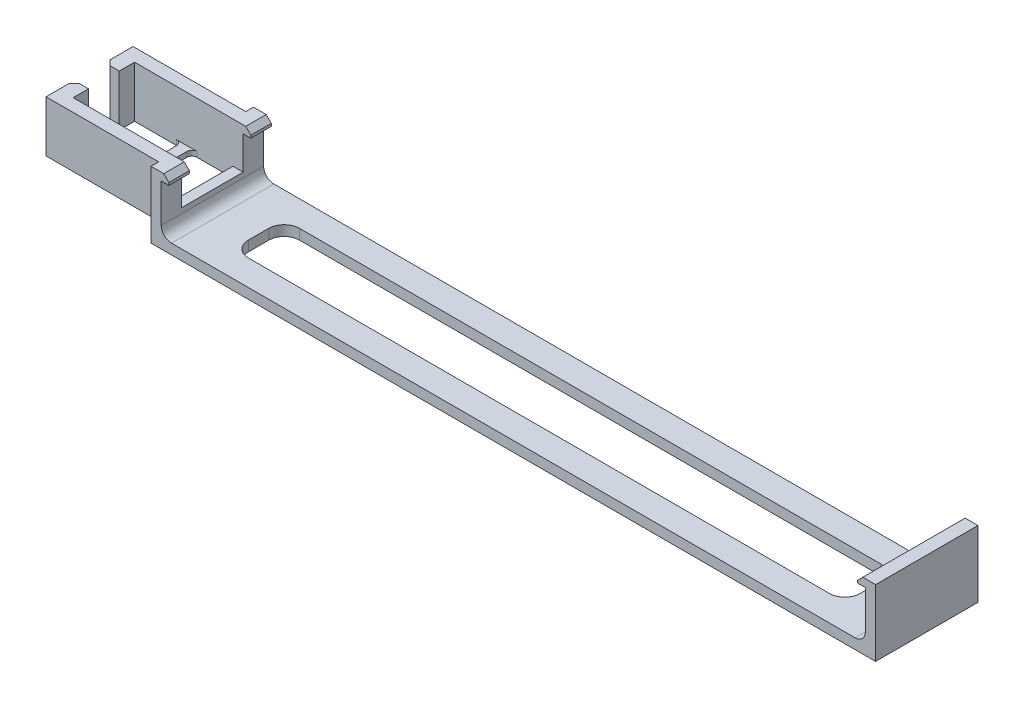
SolidWorks part; units mm, degrees
ref_plane "Front Plane" through (0, 0, 0) normal (0, 0, 1) x (1, 0, 0)
ref_plane "Top Plane" through (0, 0, 0) normal (0, 1, 0) x (1, 0, 0)
ref_plane "Right Plane" through (0, 0, 0) normal (1, 0, 0) x (0, 0, -1)
sketch "Sketch1" plane through (0, 0, 0) normal (0, 1, 0) x (1, 0, 0)
  line L1 (-70.75, 10) -> (70.75, 10)
  line L2 (-70.75, 10) -> (-70.75, -10)
  line L3 (-70.75, -10) -> (70.75, -10)
  line L4 (70.75, 10) -> (70.75, -10)
  line L5 (-70.75, 10) -> (70.75, -10) construction
  line L6 (-70.75, -10) -> (70.75, 10) construction
  point P0 (0, 0)
  dimension "D1" = 141.5
  dimension "D2" = 20
extrude "Boss-Extrude1" add sketch "Sketch1" along normal blind 2
sketch "Sketch2" plane through (0, 2, 0) normal (0, 1, 0) x (1, 0, 0)
  line L0 (-70.75, -10) -> (70.75, -10) construction
  line L1 (70.75, 10) -> (68.75, 10)
  line L2 (70.75, 10) -> (70.75, -10)
  line L3 (70.75, -10) -> (68.75, -10)
  line L4 (68.75, 10) -> (68.75, -10)
  line L6 (-70.75, 10) -> (-68.75, 10)
  line L7 (-70.75, 10) -> (-70.75, -10)
  line L8 (-70.75, -10) -> (-68.75, -10)
  line L9 (-68.75, 10) -> (-68.75, -10)
  dimension "D1" = 2
  dimension "D2" = 2
extrude "Boss-Extrude2" add sketch "Sketch2" along normal blind 11
sketch "Sketch3" plane through (68.75, 0, 0) normal (-1, 0, 0) x (0, 0, 1)
  line L0 (-10, 13) -> (-10, 2) construction
  line L1 (10, 13) -> (-10, 13)
  line L2 (10, 13) -> (10, 11.5)
  line L3 (10, 11.5) -> (-10, 11.5)
  line L4 (-10, 13) -> (-10, 11.5)
  dimension "D1" = 1.5
extrude "Boss-Extrude3" add sketch "Sketch3" along normal blind 1.5
chamfer "Chamfer1" distance 1 angle 45 1 edges at (67.25, 13, 0)
sketch "Sketch4" plane through (-68.75, 0, 0) normal (1, 0, 0) x (0, 0, -1)
  line L0 (10, 13) -> (10, 2) construction
  line L1 (-10, 13) -> (10, 13)
  line L2 (-10, 13) -> (-10, 11.5)
  line L3 (-10, 11.5) -> (10, 11.5)
  line L4 (10, 13) -> (10, 11.5)
  dimension "D1" = 1.5
extrude "Boss-Extrude4" add sketch "Sketch4" along normal blind 1.5
chamfer "Chamfer2" distance 1 angle 45 1 edges at (-67.25, 13, 0)
sketch "Sketch5" plane through (-68.75, 0, 0) normal (1, 0, 0) x (0, 0, -1)
  line L0 (-10, 11.5) -> (-10, 2) construction
  line L1 (-6, 5) -> (6, 5)
  line L2 (-6, 5) -> (-6, 19.3249)
  line L3 (-6, 19.3249) -> (6, 19.3249)
  line L4 (6, 5) -> (6, 19.3249)
  line L5 (-10, 2) -> (10, 2) construction
  dimension "D1" = 12
  dimension "D2" = 4
  dimension "D3" = 3
extrude "Cut-Extrude1" cut sketch "Sketch5" against normal blind 11.5 and the other way blind 1.5
sketch "Sketch6" plane through (-70.75, 0, 0) normal (-1, 0, 0) x (0, 0, 1)
  line L0 (-10, 13) -> (-6, 13) construction
  line L1 (-8.5, 13) -> (-6, 13)
  line L2 (-8.5, 13) -> (-8.5, 3)
  line L3 (-8.5, 3) -> (-6, 3)
  line L4 (-6, 13) -> (-6, 3)
  line L5 (6, 13) -> (10, 13) construction
  line L6 (8.5, 13) -> (6, 13)
  line L7 (8.5, 13) -> (8.5, 3)
  line L8 (8.5, 3) -> (6, 3)
  line L9 (6, 13) -> (6, 3)
  line L10 (-6, 5) -> (6, 5) construction
  line L11 (-6, 13) -> (-6, 5) construction
  dimension "D1" = 2.5
  dimension "D2" = 2.5
  dimension "D3" = 2
  dimension "D4" = 2
  dimension "D5" = 0
extrude "Boss-Extrude5" add sketch "Sketch6" along normal blind 22
sketch "Sketch7" plane through (0, 0, 6) normal (0, 0, -1) x (-1, 0, 0)
  line L0 (92.75, 3) -> (70.75, 3) construction
  line L1 (92.75, 13) -> (89.95, 13)
  line L2 (92.75, 13) -> (92.75, 3)
  line L3 (92.75, 3) -> (89.95, 3)
  line L4 (89.95, 13) -> (89.95, 3)
  dimension "D1" = 2.8
extrude "Boss-Extrude6" add sketch "Sketch7" along normal blind 3
sketch "Sketch8" plane through (0, 0, -6) normal (0, 0, 1) x (1, 0, 0)
  line L0 (-92.75, 3) -> (-70.75, 3) construction
  line L1 (-92.75, 13) -> (-89.95, 13)
  line L2 (-92.75, 13) -> (-92.75, 3)
  line L3 (-92.75, 3) -> (-89.95, 3)
  line L4 (-89.95, 13) -> (-89.95, 3)
  dimension "D1" = 2.8
extrude "Boss-Extrude7" add sketch "Sketch8" along normal blind 3
chamfer "Chamfer3" distance 1 angle 45 2 edges at (-92.75, 8, -3) (-92.75, 8, 3)
sketch "Sketch9" plane through (0, 3, 0) normal (0, -1, 0) x (1, 0, 0)
  line L0 (-92.75, 8.5) -> (-70.75, 8.5) construction
  line L1 (-80.75, 8.5) -> (-78.75, 8.5)
  line L2 (-80.75, 8.5) -> (-80.75, -8.5)
  line L3 (-80.75, -8.5) -> (-78.75, -8.5)
  line L4 (-78.75, 8.5) -> (-78.75, -8.5)
  line L5 (-92.75, -8.5) -> (-70.75, -8.5) construction
  line L6 (-70.75, -10) -> (-70.75, 10) construction
  dimension "D1" = 2
  dimension "D2" = 8
extrude "Boss-Extrude8" add sketch "Sketch9" against normal blind 1
fillet "Fillet1" radius 1 4 edges at (-80.75, 3.5, -6) (-78.75, 3.5, -6) (-80.75, 3.5, 6) (-78.75, 3.5, 6)
fillet "Fillet2" radius 2 2 edges at (-68.75, 2, 0) (68.75, 2, 0)
sketch "Sketch11" plane through (0, 2, 0) normal (0, 1, 0) x (1, 0, 0)
  line L0 (66.75, 10) -> (-66.75, 10) construction
  line L1 (-59.75, 5) -> (59.75, 5)
  line L2 (-59.75, 5) -> (-59.75, -5)
  line L3 (-59.75, -5) -> (59.75, -5)
  line L4 (59.75, 5) -> (59.75, -5)
  line L5 (-66.75, -10) -> (66.75, -10) construction
  line L6 (-66.75, 10) -> (-66.75, -10) construction
  line L7 (66.75, -10) -> (66.75, 10) construction
  dimension "D1" = 5
  dimension "D2" = 5
  dimension "D3" = 7
  dimension "D4" = 7
extrude "Cut-Extrude2" cut sketch "Sketch11" against normal blind 10
fillet "Fillet3" radius 3 4 edges at (59.75, 1, 5) (59.75, 1, -5) (-59.75, 1, 5) (-59.75, 1, -5)
